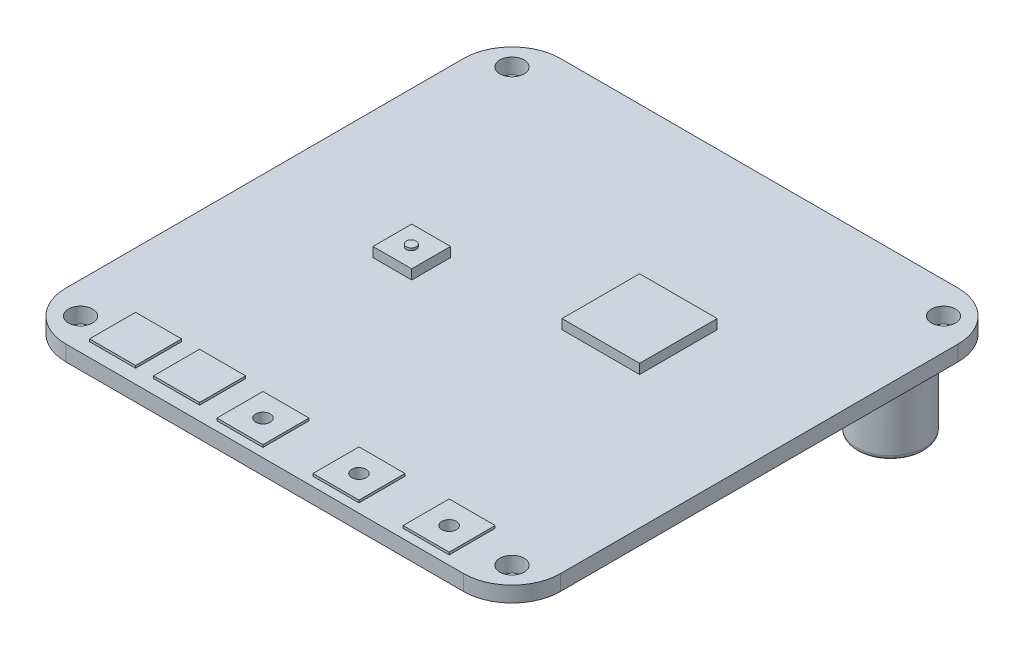
SolidWorks part; units mm, degrees
material "ABS"
ref_plane "Alzado" through (0, 0, 0) normal (0, 0, 1) x (1, 0, 0)
ref_plane "Planta" through (0, 0, 0) normal (0, 1, 0) x (1, 0, 0)
ref_plane "Vista lateral" through (0, 0, 0) normal (1, 0, 0) x (0, 0, -1)
sketch "Croquis1" plane through (0, 0, 0) normal (0, 1, 0) x (1, 0, 0)
  line L1 (-25.5, 25.5) -> (25.5, 25.5)
  line L2 (-25.5, 25.5) -> (-25.5, -25.5)
  line L3 (-25.5, -25.5) -> (25.5, -25.5)
  line L4 (25.5, 25.5) -> (25.5, -25.5)
  line L5 (-25.5, 25.5) -> (25.5, -25.5) construction
  line L6 (-25.5, -25.5) -> (25.5, 25.5) construction
  point P0 (0, 0)
  dimension "D1" = 51
  dimension "D2" = 51
extrude "Saliente-Extruir1" add sketch "Croquis1" against normal blind 1.6
fillet "Redondeo1" radius 5 4 edges at (25.5, -0.8, -25.5) (-25.5, -0.8, -25.5) (-25.5, -0.8, 25.5) (25.5, -0.8, 25.5)
sketch "Croquis2" plane through (0, 0, 0) normal (0, 1, 0) x (1, 0, 0)
  line L0 (-25.5, 20.5) -> (-25.5, -20.5) construction
  line L1 (-12.3871, 2.0474) -> (-8.3871, 2.0474)
  line L2 (-12.3871, 2.0474) -> (-12.3871, -1.9526)
  line L3 (-12.3871, -1.9526) -> (-8.3871, -1.9526)
  line L4 (-8.3871, 2.0474) -> (-8.3871, -1.9526)
  line L5 (-12.3871, 2.0474) -> (-8.3871, -1.9526) construction
  line L6 (-12.3871, -1.9526) -> (-8.3871, 2.0474) construction
  line L7 (3.8, 9.359) -> (11.8, 9.359)
  line L8 (3.8, 9.359) -> (3.8, 1.359)
  line L9 (3.8, 1.359) -> (11.8, 1.359)
  line L10 (11.8, 9.359) -> (11.8, 1.359)
  line L11 (3.8, 9.359) -> (11.8, 1.359) construction
  line L12 (3.8, 1.359) -> (11.8, 9.359) construction
  line L13 (25.5, -20.5) -> (25.5, 20.5) construction
  point P0 (-10.3871, 0.0474)
  point P5 (7.8, 5.359)
  point P12 (-25.5, 0)
  dimension "D1" = 15.113
  dimension "D2" = 4
  dimension "D3" = 8
  dimension "D4" = 17.7
extrude "Saliente-Extruir2" add sketch "Croquis2" along normal blind 1
sketch "Croquis3" plane through (0, 0, 0) normal (0, 1, 0) x (1, 0, 0)
  line L1 (22.25, 22.25) -> (-22.25, 22.25) construction
  line L2 (22.25, 22.25) -> (22.25, -22.25) construction
  line L3 (22.25, -22.25) -> (-22.25, -22.25) construction
  line L4 (-22.25, 22.25) -> (-22.25, -22.25) construction
  line L5 (22.25, 22.25) -> (-22.25, -22.25) construction
  line L6 (22.25, -22.25) -> (-22.25, 22.25) construction
  circle A0 centre (-22.25, 22.25) radius 1.25
  circle A1 centre (-22.25, -22.25) radius 1.25
  circle A2 centre (22.25, -22.25) radius 1.25
  circle A3 centre (22.25, 22.25) radius 1.25
  point P0 (0, 0)
  dimension "D2" = 2.5
  dimension "D1" = 44.5
extrude "Cortar-Extruir1" cut sketch "Croquis3" against normal through all
sketch "Croquis4" plane through (0, 0, 0) normal (0, 1, 0) x (1, 0, 0)
  line L0 (-20.5, -25.5) -> (20.5, -25.5) construction
  line L1 (-5.855, -19.825) -> (-1.105, -19.825)
  line L2 (-5.855, -19.825) -> (-5.855, -24.575)
  line L3 (-5.855, -24.575) -> (-1.105, -24.575)
  line L4 (-1.105, -19.825) -> (-1.105, -24.575)
  line L5 (-5.855, -19.825) -> (-1.105, -24.575) construction
  line L6 (-5.855, -24.575) -> (-1.105, -19.825) construction
  line L7 (4.045, -19.825) -> (8.795, -19.825)
  line L8 (4.045, -19.825) -> (4.045, -24.575)
  line L9 (4.045, -24.575) -> (8.795, -24.575)
  line L10 (8.795, -19.825) -> (8.795, -24.575)
  line L11 (4.045, -19.825) -> (8.795, -24.575) construction
  line L12 (4.045, -24.575) -> (8.795, -19.825) construction
  line L13 (13.345, -19.825) -> (18.095, -19.825)
  line L14 (13.345, -19.825) -> (13.345, -24.575)
  line L15 (13.345, -24.575) -> (18.095, -24.575)
  line L16 (18.095, -19.825) -> (18.095, -24.575)
  line L17 (13.345, -19.825) -> (18.095, -24.575) construction
  line L18 (13.345, -24.575) -> (18.095, -19.825) construction
  line L19 (25.5, -20.5) -> (25.5, 20.5) construction
  line L20 (-25.5, 20.5) -> (-25.5, -20.5) construction
  line L21 (-12.895, -19.325) -> (-8.145, -19.325)
  line L22 (-12.895, -19.325) -> (-12.895, -24.075)
  line L23 (-12.895, -24.075) -> (-8.145, -24.075)
  line L24 (-8.145, -19.325) -> (-8.145, -24.075)
  line L25 (-12.895, -19.325) -> (-8.145, -24.075) construction
  line L26 (-12.895, -24.075) -> (-8.145, -19.325) construction
  line L27 (-19.495, -19.325) -> (-14.745, -19.325)
  line L28 (-19.495, -19.325) -> (-19.495, -24.075)
  line L29 (-19.495, -24.075) -> (-14.745, -24.075)
  line L30 (-14.745, -19.325) -> (-14.745, -24.075)
  line L31 (-19.495, -19.325) -> (-14.745, -24.075) construction
  line L32 (-19.495, -24.075) -> (-14.745, -19.325) construction
  point P0 (-3.48, -22.2)
  point P5 (6.42, -22.2)
  point P10 (15.72, -22.2)
  point P17 (0, -25.5)
  point P18 (-17.12, -21.7)
  point P21 (-10.52, -21.7)
  dimension "D1" = 3.3
  dimension "D2" = 4.75
  dimension "D3" = 9.9
  dimension "D4" = 9.3
  dimension "D5" = 9.78
  dimension "D6" = 4.75
  dimension "D7" = 3.8
  dimension "D8" = 6.6
  dimension "D9" = 8.38
extrude "Saliente-Extruir3" add sketch "Croquis4" along normal blind 0.25
sketch "Croquis5" plane through (0, 0.25, 0) normal (0, 1, 0) x (1, 0, 0)
  line L0 (-1.105, -19.825) -> (-5.855, -19.825) construction
  line L1 (-5.855, -19.825) -> (-5.855, -24.575) construction
  line L2 (8.795, -19.825) -> (4.045, -19.825) construction
  line L3 (18.095, -19.825) -> (13.345, -19.825) construction
  circle A0 centre (-3.48, -22.2) radius 0.75
  circle A1 centre (6.42, -22.2) radius 0.75
  circle A2 centre (15.72, -22.2) radius 0.75
  point P9 (-3.48, -19.825)
  point P12 (-5.855, -22.2)
  point P16 (6.42, -19.825)
  point P19 (15.72, -19.825)
  dimension "D1" = 1.5
extrude "Cortar-Extruir2" cut sketch "Croquis5" against normal through all
sketch "Croquis6" plane through (0, -1.6, 0) normal (0, 1, 0) x (1, 0, 0)
  circle A0 centre (-16.2367, 22.6268) radius 3.5
  circle A1 centre (16.4107, 22.6268) radius 3.5
  dimension "D1" = 7
extrude "Saliente-Extruir4" add sketch "Croquis6" against normal blind 12
fillet "Redondeo2" radius 0.5 2 edges at (16.4107, -13.6, -19.1268) (-16.2367, -13.6, -19.1268)
sketch "Croquis7" plane through (0, -1.6, 0) normal (0, -1, 0) x (1, 0, 0)
  line L0 (-20.5, 25.5) -> (20.5, 25.5) construction
  line L1 (-22.5, -16.02) -> (15.6, -16.02)
  line L2 (-22.5, -16.02) -> (-22.5, -18.56)
  line L3 (-22.5, -18.56) -> (15.6, -18.56)
  line L4 (15.6, -16.02) -> (15.6, -18.56)
  line L5 (-22.5, -16.02) -> (15.6, -18.56) construction
  line L6 (-22.5, -18.56) -> (15.6, -16.02) construction
  line L7 (-22.5, 9.33) -> (15.6, 9.33)
  line L8 (-22.5, 9.33) -> (-22.5, 6.79)
  line L9 (-22.5, 6.79) -> (15.6, 6.79)
  line L10 (15.6, 9.33) -> (15.6, 6.79)
  line L11 (-22.5, 9.33) -> (15.6, 6.79) construction
  line L12 (-22.5, 6.79) -> (15.6, 9.33) construction
  line L13 (-25.5, -20.5) -> (-25.5, 20.5) construction
  point P0 (-3.45, -17.29)
  point P5 (-3.45, 8.06)
  dimension "D1" = 17.44
  dimension "D2" = 25.35
  dimension "D3" = 38.1
  dimension "D4" = 2.54
  dimension "D5" = 2.54
  dimension "D6" = 3
extrude "Saliente-Extruir5" add sketch "Croquis7" along normal blind 8
sketch "Croquis8" plane through (0, 1, 0) normal (0, 1, 0) x (1, 0, 0)
  line L0 (-8.3871, 2.0474) -> (-12.3871, 2.0474) construction
  circle A0 centre (-10.3871, 0) radius 0.5121
  point P5 (-10.3871, 2.0474)
extrude "Saliente-Extruir6" add sketch "Croquis8" along normal blind 0.25
